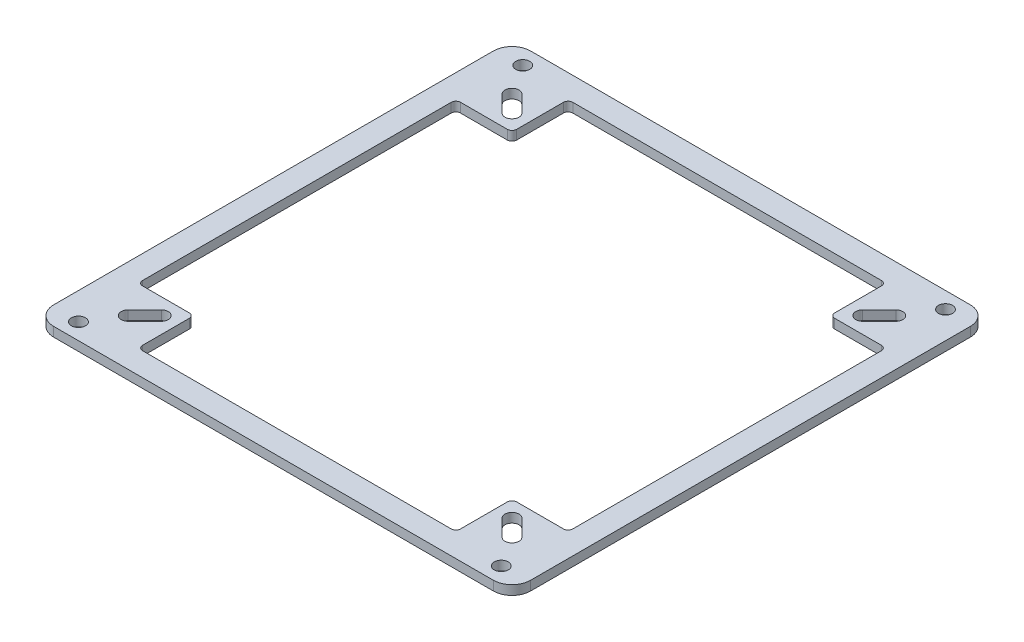
SolidWorks part; units mm, degrees
ref_plane "前视基准面" through (0, 0, 0) normal (0, 0, 1) x (1, 0, 0)
ref_plane "上视基准面" through (0, 0, 0) normal (0, 1, 0) x (1, 0, 0)
ref_plane "右视基准面" through (0, 0, 0) normal (1, 0, 0) x (0, 0, -1)
sketch "草图1" plane through (0, 0, 0) normal (0, 1, 0) x (1, 0, 0)
  line L0 (-101.4867, 55.0078) -> (-101.4867, -46.9922)
  line L1 (-95.6867, 51.5078) -> (-5.2867, 51.5078) construction
  line L2 (-95.6867, 51.5078) -> (-95.6867, -43.4922) construction
  line L3 (-95.6867, -43.4922) -> (-5.2867, -43.4922) construction
  line L4 (-5.2867, 51.5078) -> (-5.2867, -43.4922) construction
  line L5 (-101.4867, 55.0078) -> (0.5133, 55.0078) construction
  line L6 (-101.4867, 55.0078) -> (-101.4867, -46.9922) construction
  line L7 (-101.4867, -46.9922) -> (0.5133, -46.9922) construction
  line L8 (0.5133, 55.0078) -> (0.5133, -46.9922) construction
  line L18 (0.5133, 55.0078) -> (0.5133, -46.9922)
  line L24 (-101.4867, -46.9922) -> (0.5133, -46.9922)
  line L29 (-90.4867, -35.9922) -> (-10.4867, -35.9922) construction
  line L30 (-90.4867, -35.9922) -> (-90.4867, 44.0078) construction
  line L31 (-90.4867, 44.0078) -> (-10.4867, 44.0078) construction
  line L32 (-10.4867, -35.9922) -> (-10.4867, 44.0078) construction
  line L33 (-101.4867, 55.0078) -> (0.5133, 55.0078)
  circle A0 centre (-95.6867, -43.4922) radius 1.5
  circle A1 centre (-95.6867, 51.5078) radius 1.5
  circle A2 centre (-5.2867, -43.4922) radius 1.5
  circle A3 centre (-5.2867, 51.5078) radius 1.5
  circle A4 centre (-90.4867, -35.9922) radius 1
  circle A5 centre (-90.4867, 44.0078) radius 1
  circle A6 centre (-10.4867, -35.9922) radius 1
  circle A7 centre (-10.4867, 44.0078) radius 1
  dimension "D1" = 90.4
  dimension "D2" = 95
  dimension "D3" = 5.8
  dimension "D4" = 3.5
  dimension "D5" = 3.5
  dimension "D6" = 5.8
  dimension "D7" = 5.2
  dimension "D16" = 5.2
  dimension "D17" = 7.5
  dimension "D18" = 7.5
extrude "凸台-拉伸1" add sketch "草图1" along normal blind 2
sketch "草图2" plane through (0, 2, 0) normal (0, 1, 0) x (1, 0, 0)
  line L0 (-101.4867, 55.0078) -> (-101.4867, -46.9922) construction
  line L1 (-96.4867, 38.0078) -> (-4.4867, 38.0078)
  line L2 (-96.4867, 38.0078) -> (-96.4867, -29.9922)
  line L3 (-96.4867, -29.9922) -> (-4.4867, -29.9922)
  line L4 (-4.4867, 38.0078) -> (-4.4867, -29.9922)
  line L5 (0.5133, -46.9922) -> (0.5133, 55.0078) construction
  line L6 (-101.4867, -46.9922) -> (0.5133, -46.9922) construction
  line L7 (0.5133, 55.0078) -> (-101.4867, 55.0078) construction
  dimension "D1" = 5
  dimension "D2" = 5
  dimension "D3" = 17
  dimension "D4" = 17
extrude "切除-拉伸1" cut sketch "草图2" against normal blind 10
sketch "草图3" plane through (0, 2, 0) normal (0, 1, 0) x (1, 0, 0)
  line L0 (-101.4867, -46.9922) -> (0.5133, -46.9922) construction
  line L1 (-84.4867, 50.0078) -> (-16.4867, 50.0078)
  line L2 (-84.4867, 50.0078) -> (-84.4867, -41.9922)
  line L3 (-84.4867, -41.9922) -> (-16.4867, -41.9922)
  line L4 (-16.4867, 50.0078) -> (-16.4867, -41.9922)
  line L5 (0.5133, 55.0078) -> (-101.4867, 55.0078) construction
  line L6 (-101.4867, 55.0078) -> (-101.4867, -46.9922) construction
  line L7 (0.5133, -46.9922) -> (0.5133, 55.0078) construction
  dimension "D1" = 5
  dimension "D2" = 5
  dimension "D3" = 17
  dimension "D4" = 17
extrude "切除-拉伸2" cut sketch "草图3" against normal blind 10
fillet "圆角1" radius 4 4 edges at (-101.4867, 1, 46.9922) (-101.4867, 1, -55.0078) (0.5133, 1, -55.0078) (0.5133, 1, 46.9922)
sketch "草图4" plane through (0, 2, 0) normal (0, 1, 0) x (1, 0, 0)
  line L0 (-87.9867, 41.5078) -> (-91.5222, 45.0434) construction
  line L5 (-87.9867, -33.4922) -> (-91.5222, -37.0277) construction
  line L6 (-87.9867, -33.4922) -> (-12.9867, -33.4922) construction
  line L7 (-87.9867, -33.4922) -> (-87.9867, 41.5078) construction
  line L8 (-87.9867, 41.5078) -> (-12.9867, 41.5078) construction
  line L9 (-12.9867, -33.4922) -> (-12.9867, 41.5078) construction
  line L12 (-12.9867, -33.4922) -> (-9.4512, -37.0277) construction
  line L15 (-12.9867, 41.5078) -> (-9.4512, 45.0434) construction
  line L18 (-87.9867, 41.5078) -> (-91.5222, 45.0434) construction
  line L21 (-89.0474, 40.4472) -> (-92.5829, 43.9827)
  line L22 (-86.926, 42.5685) -> (-90.4616, 46.104)
  line L23 (-12.9867, 41.5078) -> (-9.4512, 45.0434) construction
  line L24 (-14.0474, 42.5685) -> (-10.5118, 46.104)
  line L25 (-11.926, 40.4472) -> (-8.3905, 43.9827)
  line L26 (-12.9867, -33.4922) -> (-9.4512, -37.0277) construction
  line L27 (-11.926, -32.4315) -> (-8.3905, -35.967)
  line L28 (-14.0474, -34.5528) -> (-10.5118, -38.0884)
  line L29 (-87.9867, -33.4922) -> (-91.5222, -37.0277) construction
  line L30 (-86.926, -34.5528) -> (-90.4616, -38.0884)
  line L31 (-89.0474, -32.4315) -> (-92.5829, -35.967)
  arc A0 (-89.0474, 40.4472) -> (-86.926, 42.5685) centre (-87.9867, 41.5078) ccw
  arc A1 (-90.4616, 46.104) -> (-92.5829, 43.9827) centre (-91.5222, 45.0434) ccw
  arc A2 (-14.0474, 42.5685) -> (-11.926, 40.4472) centre (-12.9867, 41.5078) ccw
  arc A3 (-8.3905, 43.9827) -> (-10.5118, 46.104) centre (-9.4512, 45.0434) ccw
  circle A4 centre (-90.4867, -35.9922) radius 1 construction
  circle A5 centre (-90.4867, 44.0078) radius 1 construction
  circle A6 centre (-10.4867, 44.0078) radius 1 construction
  circle A7 centre (-10.4867, -35.9922) radius 1 construction
  arc A12 (-11.926, -32.4315) -> (-14.0474, -34.5528) centre (-12.9867, -33.4922) ccw
  arc A13 (-10.5118, -38.0884) -> (-8.3905, -35.967) centre (-9.4512, -37.0277) ccw
  arc A14 (-86.926, -34.5528) -> (-89.0474, -32.4315) centre (-87.9867, -33.4922) ccw
  arc A15 (-92.5829, -35.967) -> (-90.4616, -38.0884) centre (-91.5222, -37.0277) ccw
  point P12 (-89.7545, -35.2599)
  point P19 (-11.2189, -35.2599)
  point P27 (-11.2189, 43.2756)
  point P34 (-89.7545, 43.2756)
  dimension "D4" = 2.5
  dimension "D3" = 2.5
  dimension "D1" = 2.5
  dimension "D2" = 2.5
extrude "切除-拉伸3" cut sketch "草图4" against normal blind 10
fillet "圆角2" radius 1 12 edges at (-84.4867, 1, -38.0078) (-16.4867, 1, -38.0078) (-16.4867, 1, 29.9922) (-84.4867, 1, 29.9922) (-96.4867, 1, -38.0078) (-4.4867, 1, -38.0078) (-16.4867, 1, 41.9922) (-84.4867, 1, 41.9922) (-4.4867, 1, 29.9922) (-16.4867, 1, -50.0078) (-84.4867, 1, -50.0078) (-96.4867, 1, 29.9922)
